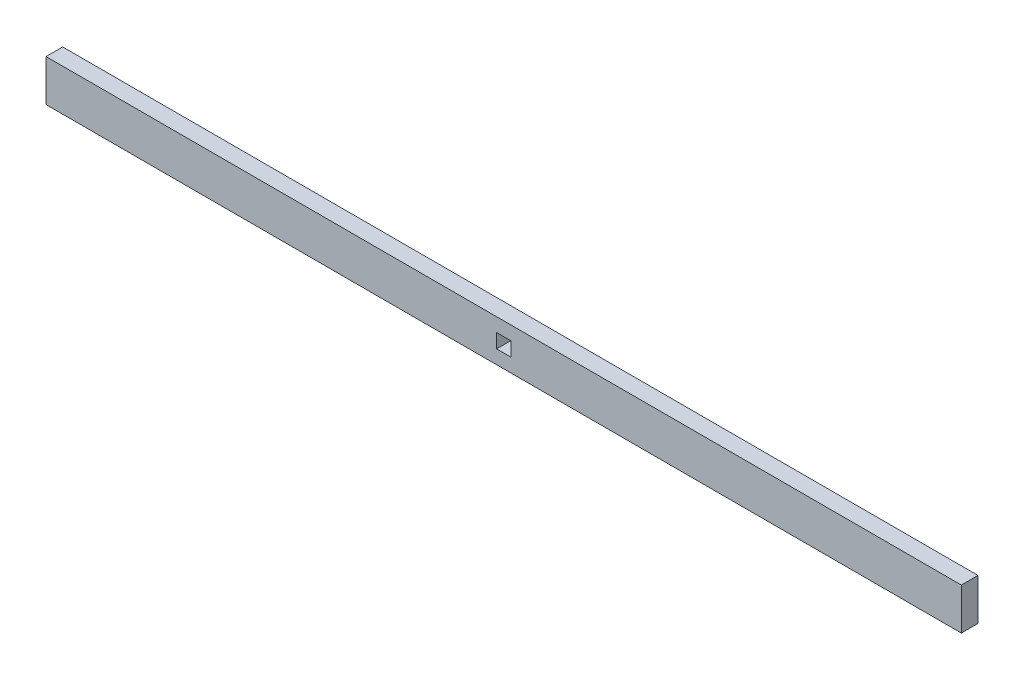
SolidWorks part; units mm, degrees
ref_plane "前视基准面" through (0, 0, 0) normal (0, 0, 1) x (1, 0, 0)
ref_plane "上视基准面" through (0, 0, 0) normal (0, 1, 0) x (1, 0, 0)
ref_plane "右视基准面" through (0, 0, 0) normal (1, 0, 0) x (0, 0, -1)
other "Configuration Table"
sketch "草图1" plane through (0, 0, 0) normal (0, 0, 1) x (1, 0, 0)
  line L1 (-550, 25) -> (550, 25)
  line L2 (-550, 25) -> (-550, -25)
  line L3 (-550, -25) -> (550, -25)
  line L4 (550, 25) -> (550, -25)
  line L5 (0, -25) -> (0, 25) construction
  line L6 (-550, 0) -> (550, 0) construction
  point P0 (0, 0)
  dimension "D1" = 1100
  dimension "D2" = 50
extrude "凸台-拉伸1" add sketch "草图1" along normal blind 20
sketch "草图2" plane through (0, 0, 20) normal (0, 0, 1) x (1, 0, 0)
  line L1 (-8.5, 8.5) -> (8.5, 8.5)
  line L2 (-8.5, 8.5) -> (-8.5, -8.5)
  line L3 (-8.5, -8.5) -> (8.5, -8.5)
  line L4 (8.5, 8.5) -> (8.5, -8.5)
  line L5 (0, -8.5) -> (0, 8.5) construction
  line L6 (-8.5, 0) -> (8.5, 0) construction
  point P0 (0, 0)
  dimension "D1" = 17
  dimension "D2" = 17
extrude "切除-拉伸1" cut sketch "草图2" against normal blind 18
